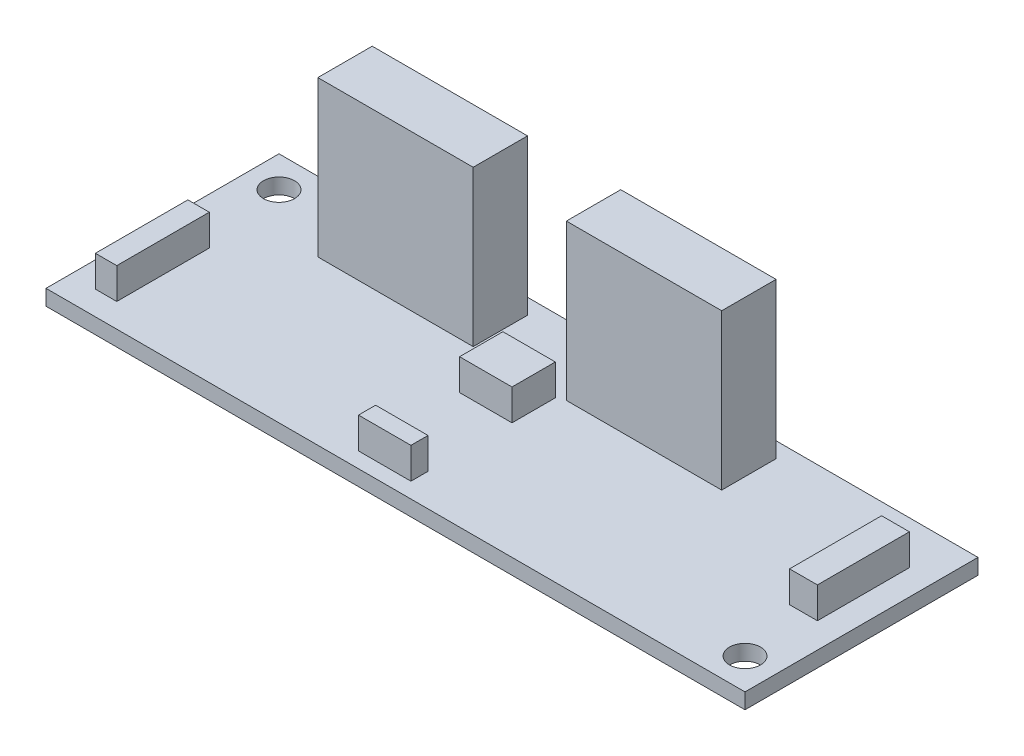
SolidWorks part; units mm, degrees
ref_plane "Front Plane" through (0, 0, 0) normal (0, 0, 1) x (1, 0, 0)
ref_plane "Top Plane" through (0, 0, 0) normal (0, 1, 0) x (1, 0, 0)
ref_plane "Right Plane" through (0, 0, 0) normal (1, 0, 0) x (0, 0, -1)
sketch "Sketch1" plane through (0, 0, 0) normal (0, 1, 0) x (1, 0, 0)
  line L1 (-22.5, -7.5) -> (22.5, -7.5)
  line L2 (-22.5, -7.5) -> (-22.5, 7.5)
  line L3 (-22.5, 7.5) -> (22.5, 7.5)
  line L4 (22.5, -7.5) -> (22.5, 7.5)
  line L5 (-22.5, -7.5) -> (22.5, 7.5) construction
  line L6 (-22.5, 7.5) -> (22.5, -7.5) construction
  circle A0 centre (-20.5, 5.5) radius 1
  circle A1 centre (20.5, -5.5) radius 1
  point P0 (0, 0)
  dimension "D3" = 2
  dimension "D8" = 2
  dimension "D1" = 45
  dimension "D2" = 15
  dimension "D4" = 2
  dimension "D5" = 2
  dimension "D6" = 2
  dimension "D7" = 2
extrude "Boss-Extrude1" add sketch "Sketch1" along normal mid plane 1
sketch "Sketch2" plane through (0, 0.5, 0) normal (0, 1, 0) x (1, 0, 0)
  line L0 (22.5, 7.5) -> (-22.5, 7.5) construction
  line L1 (-15.5, 6.5) -> (-5.5, 6.5)
  line L2 (-15.5, 6.5) -> (-15.5, 3)
  line L3 (-15.5, 3) -> (-5.5, 3)
  line L4 (-5.5, 6.5) -> (-5.5, 3)
  line L5 (-22.5, 7.5) -> (-22.5, -7.5) construction
  line L6 (0.5, 6.5) -> (10.5, 6.5)
  line L7 (0.5, 6.5) -> (0.5, 3)
  line L8 (0.5, 3) -> (10.5, 3)
  line L9 (10.5, 6.5) -> (10.5, 3)
  dimension "D1" = 1
  dimension "D2" = 10
  dimension "D3" = 7
  dimension "D4" = 3.5
  dimension "D5" = 2
extrude "Boss-Extrude2" add sketch "Sketch2" along normal blind 10
sketch "Sketch3" plane through (0, 0.5, 0) normal (0, 1, 0) x (1, 0, 0)
  line L1 (-3.3743, 2.789) -> (0, 2.789)
  line L2 (-3.3743, 2.789) -> (-3.3743, 0)
  line L3 (-3.3743, 0) -> (0, 0)
  line L4 (0, 2.789) -> (0, 0)
  line L5 (-20.8655, 0) -> (-19.4882, 0)
  line L6 (-20.8655, 0) -> (-20.8655, -5.9567)
  line L7 (-20.8655, -5.9567) -> (-19.4882, -5.9567)
  line L8 (-19.4882, 0) -> (-19.4882, -5.9567)
  line L9 (-3.3743, -5.4058) -> (0, -5.4058)
  line L10 (-3.3743, -5.4058) -> (-3.3743, -6.5076)
  line L11 (-3.3743, -6.5076) -> (0, -6.5076)
  line L12 (0, -5.4058) -> (0, -6.5076)
  line L13 (19.0751, 4.7171) -> (20.8655, 4.7171)
  line L14 (19.0751, 4.7171) -> (19.0751, -1.2051)
  line L15 (19.0751, -1.2051) -> (20.8655, -1.2051)
  line L16 (20.8655, 4.7171) -> (20.8655, -1.2051)
extrude "Boss-Extrude3" add sketch "Sketch3" along normal blind 2
